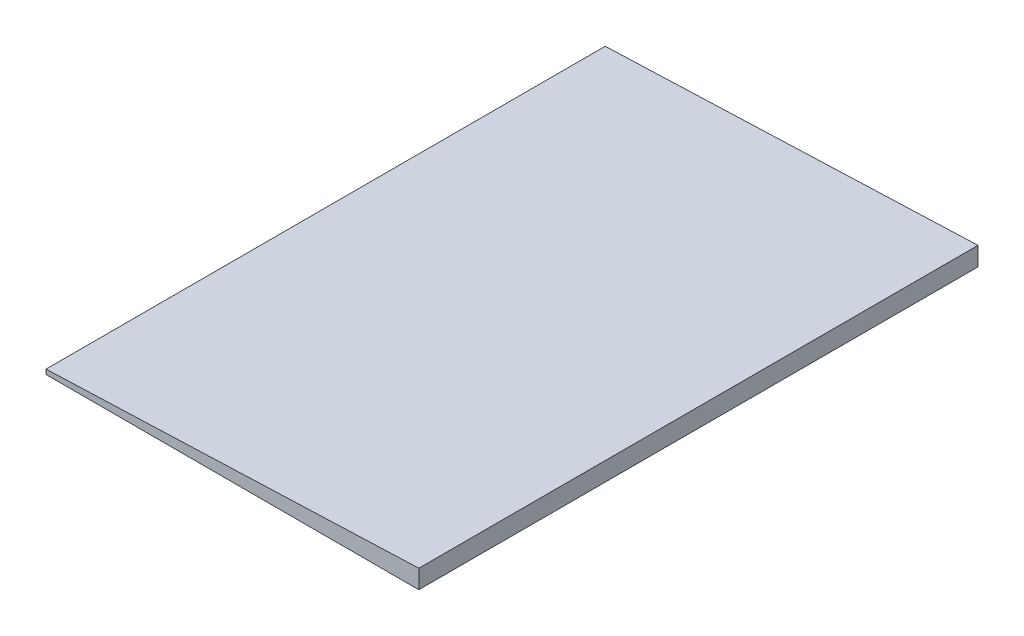
SolidWorks part; units mm, degrees
ref_plane "정면" through (0, 0, 0) normal (0, 0, 1) x (1, 0, 0)
ref_plane "윗면" through (0, 0, 0) normal (0, 1, 0) x (1, 0, 0)
ref_plane "우측면" through (0, 0, 0) normal (1, 0, 0) x (0, 0, -1)
sketch "스케치1" plane through (0, 0, 0) normal (0, 1, 0) x (1, 0, 0)
  line L1 (-52.5, 60) -> (52.5, 60)
  line L2 (-52.5, 60) -> (-52.5, -60)
  line L3 (-52.5, -60) -> (52.5, -60)
  line L4 (52.5, 60) -> (52.5, -60)
  line L5 (-52.5, 60) -> (52.5, -60) construction
  line L6 (-52.5, -60) -> (52.5, 60) construction
  point P0 (0, 0)
  dimension "D1" = 105
  dimension "D2" = 120
extrude "보스-돌출1" add sketch "스케치1" along normal blind 4
sketch "스케치4" plane through (0, 0, 60) normal (0, 0, 1) x (1, 0, 0)
  line L0 (-52.5, 0) -> (52.5, 0) construction
  line L1 (52.5, 4) -> (27.5, 4)
  line L2 (52.5, 4) -> (52.5, 0)
  line L3 (52.5, 0) -> (27.5, 0)
  line L4 (27.5, 4) -> (27.5, 0)
  line L5 (-52.5, 4) -> (-52.5, 0) construction
  dimension "D1" = 80
extrude "컷-돌출1" cut sketch "스케치4" against normal blind 155
sketch "스케치6" plane through (0, 0, 60) normal (0, 0, 1) x (1, 0, 0)
  line L0 (-52.5, 0) -> (-52.5, 1)
  line L1 (-52.5, 4) -> (-52.5, 0) construction
  line L2 (-52.5, 1) -> (27.5, 4)
  line L3 (27.5, 4) -> (27.5, 0)
  line L4 (27.5, 0) -> (-52.5, 0)
  line M3 (27.5, 4) -> (-52.5, 4)
  line M4 (-52.5, 4) -> (-52.5, 0)
  dimension "D1" = 1
extrude "컷-돌출3" cut sketch "스케치6" against normal blind 155 contours L2 M4 M3
shell "쉘1" thickness 1
